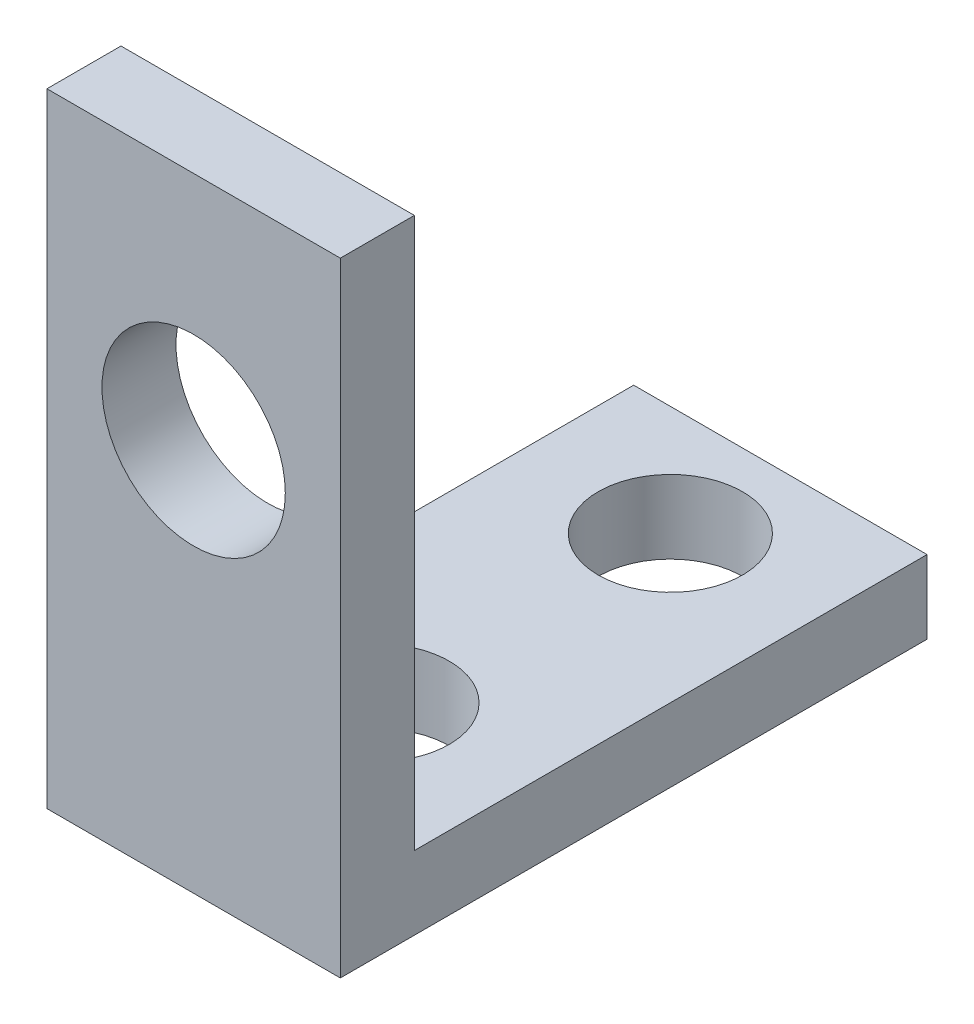
SolidWorks part; units mm, degrees
ref_plane "Front Plane" through (0, 0, 0) normal (0, 0, 1) x (1, 0, 0)
ref_plane "Top Plane" through (0, 0, 0) normal (0, 1, 0) x (1, 0, 0)
ref_plane "Right Plane" through (0, 0, 0) normal (1, 0, 0) x (0, 0, -1)
sketch "Sketch1" plane through (0, 0, 0) normal (0, 1, 0) x (1, 0, 0)
  line L0 (0, 6.35) -> (0, -3.81) construction
  line L1 (-5.08, -10.16) -> (5.08, -10.16)
  line L2 (-5.08, -10.16) -> (-5.08, 10.16)
  line L3 (-5.08, 10.16) -> (5.08, 10.16)
  line L4 (5.08, -10.16) -> (5.08, 10.16)
  line L5 (-5.08, -10.16) -> (5.08, 10.16) construction
  line L6 (-5.08, 10.16) -> (5.08, -10.16) construction
  line L7 (-5.08, 0) -> (5.08, 0) construction
  line L8 (-5.08, -7.62) -> (5.08, -7.62) construction
  circle A0 centre (0, 6.35) radius 2.5006
  circle A2 centre (0, -3.81) radius 2.5006
  point P0 (0, 0)
  point P12 (0, 0)
  dimension "D1" = 5.0013
  dimension "D2" = 6.35
  dimension "D3" = 20.32
  dimension "D4" = 3.81
  dimension "D5" = 5.08
  dimension "D6" = 3.81
  dimension "D7" = 2.54
extrude "Boss-Extrude1" add sketch "Sketch1" along normal blind 2.54
ref_plane "Plane1" through (0, 2.54, 0) normal (0, 1, 0) x (1, 0, 0)
sketch "Sketch2" plane through (0, 2.54, 0) normal (0, 1, 0) x (1, 0, 0)
  line L0 (5.08, -10.16) -> (5.08, 10.16) construction
  line L1 (-5.08, -10.16) -> (5.08, -10.16)
  line L2 (-5.08, -10.16) -> (-5.08, -7.5958)
  line L3 (-5.08, -7.5958) -> (5.08, -7.5958)
  line L4 (5.08, -10.16) -> (5.08, -7.5958)
extrude "Boss-Extrude2" add sketch "Sketch2" along normal blind 19.05
ref_plane "Plane2" through (0, 0, 10.16) normal (0, 0, 1) x (1, 0, 0)
sketch "Sketch3" plane through (0, 0, 10.16) normal (0, 0, 1) x (1, 0, 0)
  line L0 (0, 21.59) -> (0, 0) construction
  line L1 (-5.08, 21.59) -> (5.08, 21.59) construction
  line L3 (0, 10.414) -> (-5.08, 10.414) construction
  line L4 (-5.08, 21.59) -> (-5.08, 0) construction
  line L5 (0, 10.414) -> (5.08, 10.414) construction
  line L6 (5.08, 21.59) -> (5.08, 0) construction
  line L7 (-5.08, 0) -> (5.08, 0) construction
  circle A0 centre (0, 13.589) radius 3.175
  dimension "D2" = 6.35
  dimension "D1" = 10.414
  dimension "D3" = 5.08
extrude "Cut-Extrude1" cut sketch "Sketch3" against normal up to surface (2.5642 mm away) up to face at (0, 12.065, 7.5958)
